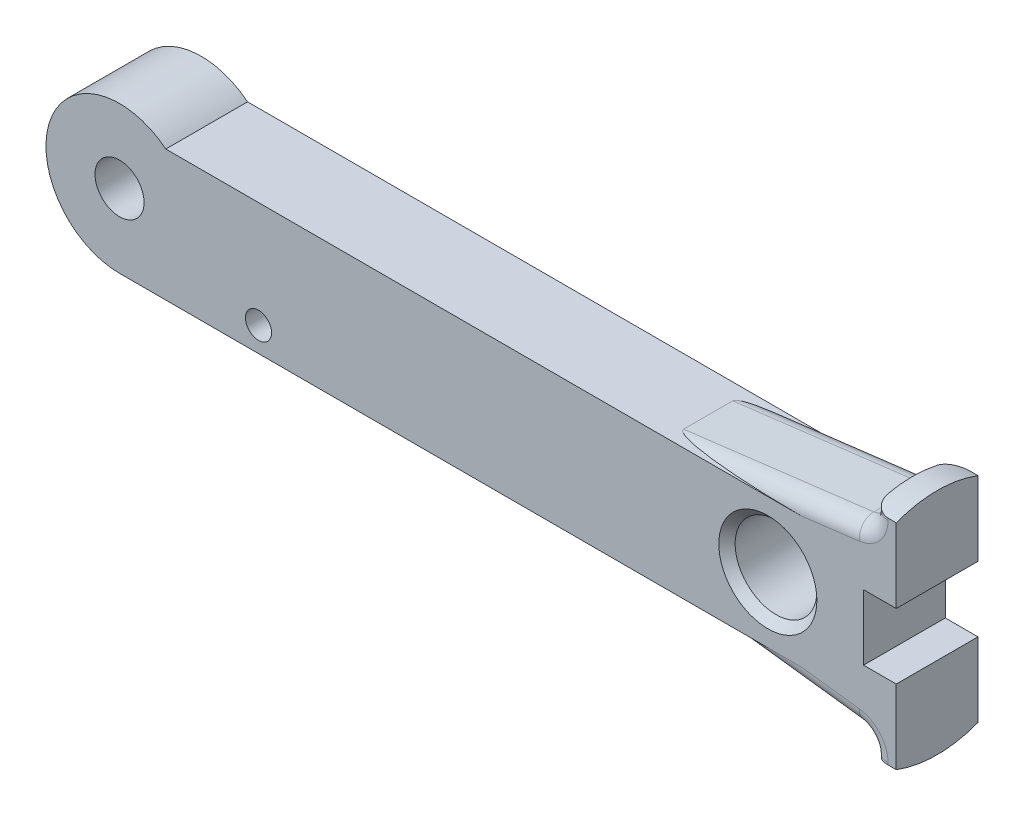
SolidWorks part; units mm, degrees
ref_plane "Front Plane" through (0, 0, 0) normal (0, 0, 1) x (1, 0, 0)
ref_plane "Top Plane" through (0, 0, 0) normal (0, 1, 0) x (1, 0, 0)
ref_plane "Right Plane" through (0, 0, 0) normal (1, 0, 0) x (0, 0, -1)
sketch "Sketch1" plane through (0, 0, 0) normal (0, 0, 1) x (1, 0, 0)
  line L0 (0, -9) -> (95, -9)
  line L1 (95, -9) -> (95, 7)
  line L2 (95, 7) -> (5.6569, 7)
  circle A0 centre (0, 0) radius 9
  dimension "D1" = 18
  dimension "D2" = 16
  dimension "D3" = 95
extrude "Boss-Extrude1" add sketch "Sketch1" along normal blind 10 contours A0 | A0 L0 L1 L2
sketch "Sketch2" plane through (0, 0, 0) normal (0, 0, 1) x (1, 0, 0)
  circle A0 centre (0, 0) radius 3
  dimension "D1" = 6
extrude "Cut-Extrude1" cut sketch "Sketch2" along normal through all
ref_plane "Plane1" through (95, 0, 0) normal (1, 0, 0) x (0, 0, -1)
sketch "Sketch4" plane through (95, 0, 0) normal (1, 0, 0) x (0, 0, -1)
  line L0 (0, -1) -> (-10, -1) construction
  line L1 (-10, -9) -> (-10, 7) construction
  line L2 (-10, -14.0767) -> (-10, 12.0767)
  line L3 (0, -14.0767) -> (0, 12.0767)
  line L4 (-5, 7) -> (-5, -9) construction
  line L5 (-10, 7) -> (0, 7) construction
  line L6 (-10, -9) -> (0, -9) construction
  circle A0 centre (-5, -1) radius 14 construction
  arc A1 (-10, 12.0767) -> (0, 12.0767) centre (-5, -1) cw
  arc A2 (0, -14.0767) -> (-10, -14.0767) centre (-5, -1) cw
  point P13 (-5, -1)
  point P19 (-5, -1)
  point P20 (-0.3379, 12.2009)
  dimension "D1" = 28
extrude "Boss-Extrude2" add sketch "Sketch4" against normal blind 3 contours A2 L3 A1 L2
sketch "Sketch3" plane through (0, 0, 0) normal (0, 0, 1) x (1, 0, 0)
  line L0 (95, 3) -> (91, 3)
  line L1 (95, -14.0767) -> (95, 12.0767) construction
  line L2 (91, 3) -> (91, -5)
  line L3 (91, -5) -> (95, -5)
  line L4 (95, -5) -> (95, 3)
  line L6 (95, -14.0767) -> (95, 12.0767) construction
  point P8 (95, -1)
  point P9 (95, -1)
  dimension "D1" = 8
  dimension "D2" = 4
extrude "Cut-Extrude2" cut sketch "Sketch3" along normal through all
sketch "Sketch5" plane through (0, 0, 10) normal (0, 0, 1) x (1, 0, 0)
  line L0 (92, 10.0767) -> (67, 7)
  line L1 (92, 7) -> (92, 12.0767) construction
  line L2 (92, 7) -> (5.6569, 7) construction
  point P6 (67.9436, 7)
  dimension "D1" = 2
  dimension "D2" = 25
rib "Rib4" sketch "Sketch5" sketch "Sketch5" thickness 10 extrusion direction parallel to sketch draft on no parameters "D1"=10
fillet "Fillet1" radius 2 5 edges at (79.5, 8.5383, 0) (79.5, 8.5383, 10) (92, 11.0767, 0) (92, 11.0767, 10) (92, 10.0767, 5)
ref_plane "Plane2" through (0, -1, 0) normal (0, 1, 0) x (1, 0, 0)
mirror "Mirror1" about plane through (0, -1, 0) normal (0, 1, 0) of "Fillet1", "Rib4"
sketch "Sketch7" plane through (0, 0, 0) normal (0, 0, 1) x (1, 0, 0)
  line L0 (5.5, -1) -> (-5.5, -1) construction
  circle A0 centre (79.2948, -1) radius 5
  point P2 (0, 0)
  dimension "D1" = 10
extrude "Cut-Extrude3" cut sketch "Sketch7" along normal through all
chamfer "Chamfer1" distance 1 angle 45 2 edges at (84.2948, -1, 10) (84.2948, -1, 0)
hole_wizard "CSK for M3 Flat Head Machine Screw1" positions "Sketch8" profile "Sketch9" countersink size "M3" standard "ANSI Metric" end condition through all
sketch "Sketch8" plane through (0, 0, 0) normal (0, 0, -1) x (-1, 0, 0)
  point P0 (-17, -6)
  dimension "D1" = 17
  dimension "D2" = 6
sketch "Sketch9" plane through (17, -6, 0) normal (1, 0, 0) x (0, 1, 0)
  line L0 (0, 0) -> (0, 10)
  line L1 (0, 10) -> (1.6, 10)
  line L2 (1.6, 10) -> (1.6, 1.55)
  line L3 (1.6, 1.55) -> (3.15, 0)
  line L5 (3.15, 0) -> (0, 0)
  line L6 (-1.6, 1.55) -> (-3.15, 0) construction
  line L11 (0, -6.35) -> (0, 107.95) construction
  dimension "Thru Hole Dia." = 3.2
  dimension "Thru Hole Depth" = 10
  dimension "Near C'Sink Dia." = 6.3
  dimension "Near C'Sink Angle" = 90
